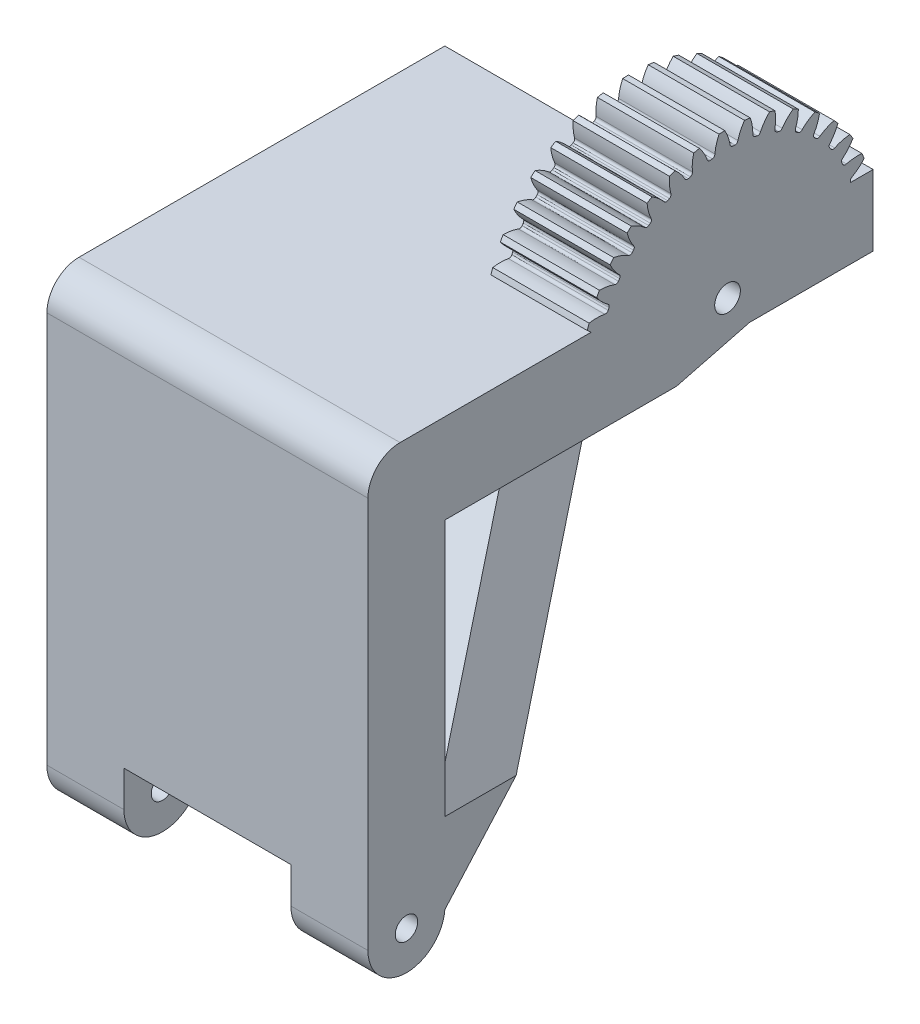
SolidWorks part; units mm, degrees
ref_plane "Front Plane" through (0, 0, 0) normal (0, 0, 1) x (1, 0, 0)
ref_plane "Top Plane" through (0, 0, 0) normal (0, 1, 0) x (1, 0, 0)
ref_plane "Right Plane" through (0, 0, 0) normal (1, 0, 0) x (0, 0, -1)
other "Graphic1"
sketch "Sketch2" plane through (0, 0, 0) normal (1, 0, 0) x (0, 0, -1)
  line L0 (-282, -50) -> (-282, 16.0062)
  line L1 (-282, 16.0062) -> (-203.3277, 16.0062)
  line L2 (-203.3277, 16.0062) -> (-203.3277, 4.9936)
  line L3 (-203.3277, 4.9936) -> (-222.5466, 4.9936)
  line L4 (-222.5466, 4.9936) -> (-233.9331, 2.0714)
  line L5 (-233.9331, 2.0714) -> (-233.9331, -9.6765)
  line L6 (-233.9331, -9.6765) -> (-270.0186, -50.4726)
  line L7 (-270.0186, 2.0714) -> (-270.0186, -35.8156)
  line L8 (-270.0186, -35.8156) -> (-240.3653, -2.4074)
  line L10 (-240.3653, -2.4074) -> (-240.3737, 1.8611)
  line L11 (-240.3737, 1.8611) -> (-270.0186, 2.0714)
  circle A0 centre (-276, -50) radius 1.75
  circle A1 centre (-226, 10) radius 2
  arc A2 (-282, -50) -> (-270.0186, -50.4726) centre (-276, -50) ccw
  point P24 (0, 0)
  point P25 (0, 0)
  point P26 (0, 0)
  point P29 (0, 0)
  point P32 (0, 0)
extrude "Boss-Extrude1" add sketch "Sketch2" along normal blind 47.5 and the other way blind 2.5 from offset 70
sketch "Sketch3" plane through (0, 0, 0) normal (0, 0, 1) x (1, 0, 0)
  line L0 (79.5, -55.8916) -> (79.5, -57.717)
  line L2 (79.5, -55.8916) -> (79.5, -44.4098)
  line L3 (79.5, -44.4098) -> (105.5, -44.4098)
  line L4 (105.5, -55.8916) -> (105.5, -44.4098)
  line L5 (79.5, -57.717) -> (105.5, -57.717)
  line L6 (105.5, -57.717) -> (105.5, -55.8916)
  point P8 (0, 0)
  point P9 (0, 0)
extrude "Cut-Extrude1" cut sketch "Sketch3" along normal through all
sketch "Sketch4" plane through (0, 0, 0) normal (0, 0, 1) x (1, 0, 0)
  line L0 (105.5, -44.4098) -> (94.3961, -22.2019)
  line L3 (90.6039, -22.2019) -> (79.5, -44.4098)
  line L4 (79.5, -44.4098) -> (105.5, -44.4098)
  line L5 (97.5, 2.0714) -> (117.5, -37.9286)
  line L6 (67.5, 2.0714) -> (117.5, 2.0714) construction
  line L7 (117.5, -50.4726) -> (117.5, -9.6765) construction
  line L8 (117.5, 2.0714) -> (97.5, 2.0714)
  line L9 (87.5, 2.0714) -> (67.5, 2.0714)
  line L10 (67.5, -9.6765) -> (67.5, 2.0714) construction
  line L11 (67.5, 2.0714) -> (67.5, -37.9286)
  line L12 (67.5, -50.4726) -> (67.5, -9.6765) construction
  line L13 (67.5, -37.9286) -> (87.5, 2.0714)
  line L14 (117.5, 2.0714) -> (117.5, -37.9286)
  line L15 (92.5, 16.0062) -> (92.5, -62.4116) construction
  line L16 (67.5, 16.0062) -> (117.5, 16.0062) construction
  line L17 (67.5, 16.0062) -> (67.5, -50) construction
  line L18 (117.5, 16.0062) -> (117.5, -50) construction
  arc A0 (94.3961, -22.2019) -> (90.6039, -22.2019) centre (92.5, -23.15) ccw
  dimension "D1" = 25
  dimension "D2" = 25
  dimension "D3" = 20
  dimension "D4" = 20
  dimension "D5" = 40
  dimension "D6" = 40
extrude "Cut-Extrude2" cut sketch "Sketch4" against normal blind 53 from surface at 270.0186 starting at face at (92.5, -16.8721, 270.0186)
fillet "Fillet1" radius 5 1 edges at (92.5, 16.0062, 282)
sketch "Sketch5" plane through (0, 16.0062, 0) normal (0, 1, 0) x (1, 0, 0)
  line L0 (65.0251, -220.0274) -> (95.5, -220.0314)
  line L1 (95.5, -220.0314) -> (102.5, -213.068)
  line L2 (102.5, -213.068) -> (102.5, -196.177)
  line L3 (102.5, -196.177) -> (65.0251, -196.177)
  line L4 (65.0251, -196.177) -> (65.0251, -220.0274)
  point P7 (0, 0)
  point P8 (0, 0)
extrude "Cut-Extrude3" cut sketch "Sketch5" against normal through all
sketch "Sketch7" plane through (117.5, 0, 0) normal (1, 0, 0) x (0, 0, -1)
  line L5 (-247.2493, 16.0062) -> (-206.8184, 16.0062)
  arc A0 (-222.9056, 32.589) -> (-222.459, 32.5234) centre (-226, 10) cw
  arc A1 (-221.7033, 29.6354) -> (-221.3907, 29.5644) centre (-226, 10) cw
  arc A2 (-219.0301, 31.7085) -> (-219.4613, 31.8423) centre (-226, 10) ccw
  arc A3 (-219.0301, 31.7085) -> (-218.6017, 31.5663) centre (-226, 10) cw
  arc A4 (-218.3589, 28.591) -> (-218.0634, 28.4667) centre (-226, 10) cw
  arc A5 (-215.3663, 30.1684) -> (-215.7678, 30.375) centre (-226, 10) ccw
  arc A6 (-215.3663, 30.1684) -> (-214.9691, 29.9539) centre (-226, 10) cw
  arc A7 (-215.2467, 26.9817) -> (-214.9773, 26.808) centre (-226, 10) cw
  arc A8 (-212.0257, 28.0155) -> (-212.3851, 28.2887) centre (-226, 10) ccw
  arc A9 (-212.0257, 28.0155) -> (-211.6717, 27.7353) centre (-226, 10) cw
  arc A10 (-212.4612, 24.8564) -> (-212.226, 24.6386) centre (-226, 10) cw
  arc A11 (-209.1096, 25.3152) -> (-209.4162, 25.6466) centre (-226, 10) ccw
  arc A12 (-209.1096, 25.3152) -> (-208.8097, 24.9778) centre (-226, 10) cw
  arc A13 (-210.0871, 22.2797) -> (-209.8933, 22.0244) centre (-226, 10) cw
  arc A14 (-206.7068, 22.1495) -> (-206.9511, 22.5292) centre (-226, 10) ccw
  arc A15 (-206.7068, 22.1495) -> (-206.47, 21.7652) centre (-226, 10) cw
  arc A16 (-208.1966, 19.3299) -> (-208.05, 19.0448) centre (-226, 10) cw
  arc A17 (-204.8901, 18.6147) -> (-205.0648, 19.031) centre (-226, 10) ccw
  arc A18 (-204.8901, 18.6147) -> (-204.7237, 18.1951) centre (-226, 10) cw
  arc A19 (-206.8469, 16.0966) -> (-206.8184, 16.0062) centre (-226, 10) cw
  arc A83 (-247.7085, 16.9699) -> (-247.8423, 16.5387) centre (-226, 10) ccw
  arc A84 (-247.7085, 16.9699) -> (-247.5663, 17.3984) centre (-226, 10) cw
  arc A85 (-244.591, 17.6411) -> (-244.4667, 17.9366) centre (-226, 10) cw
  arc A86 (-246.1684, 20.6337) -> (-246.375, 20.2323) centre (-226, 10) ccw
  arc A87 (-246.1684, 20.6337) -> (-245.9539, 21.0309) centre (-226, 10) cw
  arc A88 (-242.9817, 20.7533) -> (-242.808, 21.0228) centre (-226, 10) cw
  arc A89 (-244.0155, 23.9743) -> (-244.2887, 23.6149) centre (-226, 10) ccw
  arc A90 (-244.0155, 23.9743) -> (-243.7353, 24.3283) centre (-226, 10) cw
  arc A91 (-240.8564, 23.5388) -> (-240.6386, 23.774) centre (-226, 10) cw
  arc A92 (-241.3152, 26.8904) -> (-241.6466, 26.5838) centre (-226, 10) ccw
  arc A93 (-241.3152, 26.8904) -> (-240.9778, 27.1903) centre (-226, 10) cw
  arc A94 (-238.2797, 25.9129) -> (-238.0244, 26.1067) centre (-226, 10) cw
  arc A95 (-238.1495, 29.2932) -> (-238.5292, 29.0489) centre (-226, 10) ccw
  arc A96 (-238.1495, 29.2932) -> (-237.7652, 29.53) centre (-226, 10) cw
  arc A97 (-235.3299, 27.8035) -> (-235.0448, 27.95) centre (-226, 10) cw
  arc A98 (-234.6147, 31.1099) -> (-235.031, 30.9352) centre (-226, 10) ccw
  arc A99 (-234.6147, 31.1099) -> (-234.1951, 31.2763) centre (-226, 10) cw
  arc A100 (-232.0966, 29.1531) -> (-231.7904, 29.2479) centre (-226, 10) cw
  arc A101 (-230.8182, 32.2851) -> (-231.2585, 32.1853) centre (-226, 10) ccw
  arc A102 (-230.8182, 32.2851) -> (-230.376, 32.3761) centre (-226, 10) cw
  arc A103 (-228.6781, 29.9208) -> (-228.3601, 29.961) centre (-226, 10) cw
  arc A104 (-226.8752, 32.7832) -> (-227.3261, 32.7614) centre (-226, 10) ccw
  arc A105 (-226.8752, 32.7832) -> (-226.4239, 32.7961) centre (-226, 10) cw
  arc A106 (-225.1782, 30.0832) -> (-224.858, 30.0675) centre (-226, 10) cw
  arc A107 (-222.9056, 32.589) -> (-223.3535, 32.6459) centre (-226, 10) ccw
  arc A108 (-206.0792, 12.6781) -> (-206.039, 12.3601) centre (-226, 10) cw [skipped]
  arc A109 (-203.2168, 10.8752) -> (-203.2386, 11.3261) centre (-226, 10) ccw [skipped]
  arc A110 (-203.2168, 10.8752) -> (-203.2039, 10.4239) centre (-226, 10) cw [skipped]
  arc A111 (-205.9168, 9.1782) -> (-205.9325, 8.858) centre (-226, 10) cw [skipped]
  arc A112 (-203.411, 6.9056) -> (-203.3541, 7.3535) centre (-226, 10) ccw [skipped]
  arc A113 (-203.411, 6.9056) -> (-203.4767, 6.459) centre (-226, 10) cw [skipped]
  arc A114 (-206.3646, 5.7033) -> (-206.4356, 5.3907) centre (-226, 10) cw [skipped]
  arc A115 (-204.2915, 3.0301) -> (-204.1577, 3.4613) centre (-226, 10) ccw [skipped]
  arc A116 (-204.2915, 3.0301) -> (-204.4337, 2.6017) centre (-226, 10) cw [skipped]
  arc A117 (-207.4091, 2.3589) -> (-207.5333, 2.0634) centre (-226, 10) cw [skipped]
  arc A118 (-205.8316, -0.6337) -> (-205.625, -0.2322) centre (-226, 10) ccw [skipped]
  arc A119 (-205.8316, -0.6337) -> (-206.0461, -1.0309) centre (-226, 10) cw [skipped]
  arc A120 (-209.0184, -0.7533) -> (-209.192, -1.0227) centre (-226, 10) cw [skipped]
  arc A121 (-207.9845, -3.9743) -> (-207.7114, -3.6149) centre (-226, 10) ccw [skipped]
  arc A122 (-207.9845, -3.9743) -> (-208.2647, -4.3283) centre (-226, 10) cw [skipped]
  arc A123 (-211.1436, -3.5388) -> (-211.3614, -3.774) centre (-226, 10) cw [skipped]
  arc A124 (-210.6848, -6.8904) -> (-210.3534, -6.5838) centre (-226, 10) ccw [skipped]
  arc A125 (-210.6848, -6.8904) -> (-211.0222, -7.1903) centre (-226, 10) cw [skipped]
  arc A126 (-213.7203, -5.9129) -> (-213.9757, -6.1067) centre (-226, 10) cw [skipped]
  arc A127 (-213.8505, -9.2932) -> (-213.4709, -9.0489) centre (-226, 10) ccw [skipped]
  arc A128 (-213.8505, -9.2932) -> (-214.2348, -9.53) centre (-226, 10) cw [skipped]
  arc A129 (-216.6701, -7.8035) -> (-216.9552, -7.95) centre (-226, 10) cw [skipped]
  arc A130 (-217.3853, -11.1099) -> (-216.969, -10.9352) centre (-226, 10) ccw [skipped]
  arc A131 (-217.3853, -11.1099) -> (-217.8049, -11.2763) centre (-226, 10) cw [skipped]
  arc A132 (-219.9034, -9.1531) -> (-220.2096, -9.2479) centre (-226, 10) cw [skipped]
  arc A133 (-221.1818, -12.2851) -> (-220.7416, -12.1853) centre (-226, 10) ccw [skipped]
  arc A134 (-221.1818, -12.2851) -> (-221.624, -12.3761) centre (-226, 10) cw [skipped]
  arc A135 (-223.3219, -9.9208) -> (-223.6399, -9.961) centre (-226, 10) cw [skipped]
  arc A136 (-225.1248, -12.7832) -> (-224.6739, -12.7614) centre (-226, 10) ccw [skipped]
  arc A137 (-225.1248, -12.7832) -> (-225.5761, -12.7961) centre (-226, 10) cw [skipped]
  arc A138 (-226.8218, -10.0832) -> (-227.142, -10.0675) centre (-226, 10) cw [skipped]
  arc A139 (-229.0944, -12.589) -> (-228.6465, -12.6459) centre (-226, 10) ccw [skipped]
  arc A140 (-229.0944, -12.589) -> (-229.541, -12.5233) centre (-226, 10) cw [skipped]
  arc A141 (-230.2967, -9.6354) -> (-230.6093, -9.5644) centre (-226, 10) cw [skipped]
  arc A142 (-232.9699, -11.7085) -> (-232.5387, -11.8423) centre (-226, 10) ccw [skipped]
  arc A143 (-232.9699, -11.7085) -> (-233.3984, -11.5663) centre (-226, 10) cw [skipped]
  arc A144 (-233.6411, -8.591) -> (-233.9366, -8.4667) centre (-226, 10) cw [skipped]
  arc A145 (-236.6337, -10.1684) -> (-236.2323, -10.375) centre (-226, 10) ccw [skipped]
  arc A146 (-236.6337, -10.1684) -> (-237.0309, -9.9539) centre (-226, 10) cw [skipped]
  arc A147 (-236.7533, -6.9817) -> (-237.0228, -6.808) centre (-226, 10) cw [skipped]
  arc A148 (-239.9743, -8.0155) -> (-239.6149, -8.2887) centre (-226, 10) ccw [skipped]
  arc A149 (-239.9743, -8.0155) -> (-240.3283, -7.7353) centre (-226, 10) cw [skipped]
  arc A150 (-239.5388, -4.8564) -> (-239.774, -4.6386) centre (-226, 10) cw [skipped]
  arc A151 (-242.8904, -5.3152) -> (-242.5838, -5.6466) centre (-226, 10) ccw [skipped]
  arc A152 (-242.8904, -5.3152) -> (-243.1903, -4.9778) centre (-226, 10) cw [skipped]
  arc A153 (-241.9129, -2.2797) -> (-242.1067, -2.0244) centre (-226, 10) cw [skipped]
  arc A154 (-245.2932, -2.1495) -> (-245.0489, -2.5291) centre (-226, 10) ccw [skipped]
  arc A155 (-245.2932, -2.1495) -> (-245.53, -1.7652) centre (-226, 10) cw [skipped]
  arc A156 (-243.8035, 0.6701) -> (-243.95, 0.9552) centre (-226, 10) cw [skipped]
  arc A157 (-247.1099, 1.3853) -> (-246.9352, 0.969) centre (-226, 10) ccw [skipped]
  arc A158 (-247.1099, 1.3853) -> (-247.2763, 1.8049) centre (-226, 10) cw [skipped]
  arc A159 (-245.1531, 3.9034) -> (-245.2479, 4.2096) centre (-226, 10) cw [skipped]
  arc A160 (-248.2851, 5.1818) -> (-248.1853, 4.7416) centre (-226, 10) ccw [skipped]
  arc A161 (-248.2851, 5.1818) -> (-248.3761, 5.624) centre (-226, 10) cw [skipped]
  arc A162 (-245.9208, 7.3219) -> (-245.961, 7.6399) centre (-226, 10) cw [skipped]
  arc A163 (-248.7832, 9.1248) -> (-248.7614, 8.6739) centre (-226, 10) ccw [skipped]
  arc A164 (-248.7832, 9.1248) -> (-248.7961, 9.5761) centre (-226, 10) cw [skipped]
  arc A165 (-246.0832, 10.8218) -> (-246.0675, 11.142) centre (-226, 10) cw [skipped]
  arc A166 (-248.5891, 13.0944) -> (-248.6459, 12.6465) centre (-226, 10) ccw [skipped]
  arc A167 (-248.5891, 13.0944) -> (-248.5234, 13.541) centre (-226, 10) cw [skipped]
  arc A168 (-245.6354, 14.2967) -> (-245.5644, 14.6093) centre (-226, 10) cw [skipped]
  arc A169 (-203.7149, 14.8182) -> (-203.8147, 15.2584) centre (-226, 10) ccw [skipped]
  arc A170 (-203.7149, 14.8182) -> (-203.6239, 14.376) centre (-226, 10) cw [skipped]
  spline S0 degree 2 poles (-222.459, 32.5234) (-222.0472, 31.3598) (-222.0503, 30.123) knots 0 0 0 1 1 1
  spline S1 degree 2 poles (-222.0503, 30.123) (-222.0649, 29.7407) (-221.7033, 29.6354) knots 0 0 0 1 1 1
  spline S2 degree 2 poles (-220.867, 29.8542) (-221.019, 29.503) (-221.3907, 29.5644) knots 0 0 0 1 1 1
  spline S3 degree 2 poles (-219.4613, 31.8423) (-220.3354, 30.9709) (-220.867, 29.8542) knots 0 0 0 1 1 1
  spline S4 degree 2 poles (-218.6017, 31.5663) (-218.3982, 30.3489) (-218.616, 29.1315) knots 0 0 0 1 1 1
  spline S5 degree 2 poles (-218.616, 29.1315) (-218.6968, 28.7574) (-218.3589, 28.591) knots 0 0 0 1 1 1
  spline S6 degree 2 poles (-217.4973, 28.6612) (-217.708, 28.3418) (-218.0634, 28.4667) knots 0 0 0 1 1 1
  spline S7 degree 2 poles (-215.7678, 30.375) (-216.7799, 29.6687) (-217.4973, 28.6612) knots 0 0 0 1 1 1
  spline S8 degree 2 poles (-214.9691, 29.9539) (-214.9801, 28.7197) (-215.4061, 27.5586) knots 0 0 0 1 1 1
  spline S9 degree 2 poles (-215.4061, 27.5586) (-215.5506, 27.2043) (-215.2467, 26.9817) knots 0 0 0 1 1 1
  spline S10 degree 2 poles (-214.386, 26.9012) (-214.649, 26.6233) (-214.9773, 26.808) knots 0 0 0 1 1 1
  spline S11 degree 2 poles (-212.3851, 28.2887) (-213.5046, 27.7688) (-214.386, 26.9012) knots 0 0 0 1 1 1
  spline S12 degree 2 poles (-211.6717, 27.7353) (-211.8969, 26.5217) (-212.518, 25.4522) knots 0 0 0 1 1 1
  spline S13 degree 2 poles (-212.518, 25.4522) (-212.7218, 25.1284) (-212.4612, 24.8564) knots 0 0 0 1 1 1
  spline S14 degree 2 poles (-211.6276, 24.6277) (-211.9348, 24.3996) (-212.226, 24.6386) knots 0 0 0 1 1 1
  spline S15 degree 2 poles (-209.4162, 25.6466) (-210.6089, 25.329) (-211.6276, 24.6277) knots 0 0 0 1 1 1
  spline S16 degree 2 poles (-208.8097, 24.9778) (-209.2422, 23.8217) (-210.0396, 22.8763) knots 0 0 0 1 1 1
  spline S17 degree 2 poles (-210.0396, 22.8763) (-210.2965, 22.5928) (-210.0871, 22.2797) knots 0 0 0 1 1 1
  spline S18 degree 2 poles (-209.3059, 21.9097) (-209.6481, 21.7385) (-209.8933, 22.0244) knots 0 0 0 1 1 1
  spline S19 degree 2 poles (-206.9511, 22.5292) (-208.1808, 22.4235) (-209.3059, 21.9097) knots 0 0 0 1 1 1
  spline S20 degree 2 poles (-206.47, 21.7652) (-207.0966, 20.7018) (-208.0461, 19.9092) knots 0 0 0 1 1 1
  spline S21 degree 2 poles (-208.0461, 19.9092) (-208.3484, 19.6746) (-208.1966, 19.3299) knots 0 0 0 1 1 1
  spline S22 degree 2 poles (-207.4914, 18.8299) (-207.8581, 18.7207) (-208.05, 19.0448) knots 0 0 0 1 1 1
  spline S23 degree 2 poles (-205.0648, 19.031) (-206.2942, 19.1405) (-207.4914, 18.8299) knots 0 0 0 1 1 1
  spline S24 degree 2 poles (-204.7237, 18.1951) (-205.5255, 17.2567) (-206.5981, 16.641) knots 0 0 0 1 1 1
  spline S25 degree 2 poles (-206.5981, 16.641) (-206.9366, 16.4625) (-206.8469, 16.0966) knots 0 0 0 1 1 1
  spline S111 degree 2 poles (-247.8423, 16.5387) (-247.5588, 16.2543) (-247.2493, 16.0062) knots 0 0 0 0.325355 0.325355 0.325355
  spline S112 degree 2 poles (-247.5663, 17.3984) (-246.3489, 17.6019) (-245.1315, 17.384) knots 0 0 0 1 1 1
  spline S113 degree 2 poles (-245.1315, 17.384) (-244.7574, 17.3032) (-244.591, 17.6411) knots 0 0 0 1 1 1
  spline S114 degree 2 poles (-244.6612, 18.5027) (-244.3418, 18.292) (-244.4667, 17.9366) knots 0 0 0 1 1 1
  spline S115 degree 2 poles (-246.375, 20.2323) (-245.6687, 19.2201) (-244.6612, 18.5027) knots 0 0 0 1 1 1
  spline S116 degree 2 poles (-245.9539, 21.0309) (-244.7197, 21.0199) (-243.5586, 20.594) knots 0 0 0 1 1 1
  spline S117 degree 2 poles (-243.5586, 20.594) (-243.2043, 20.4494) (-242.9817, 20.7533) knots 0 0 0 1 1 1
  spline S118 degree 2 poles (-242.9012, 21.614) (-242.6233, 21.351) (-242.808, 21.0228) knots 0 0 0 1 1 1
  spline S119 degree 2 poles (-244.2887, 23.6149) (-243.7688, 22.4954) (-242.9012, 21.614) knots 0 0 0 1 1 1
  spline S120 degree 2 poles (-243.7353, 24.3283) (-242.5217, 24.1031) (-241.4522, 23.482) knots 0 0 0 1 1 1
  spline S121 degree 2 poles (-241.4522, 23.482) (-241.1284, 23.2782) (-240.8564, 23.5388) knots 0 0 0 1 1 1
  spline S122 degree 2 poles (-240.6277, 24.3724) (-240.3996, 24.0652) (-240.6386, 23.774) knots 0 0 0 1 1 1
  spline S123 degree 2 poles (-241.6466, 26.5838) (-241.3291, 25.3911) (-240.6277, 24.3724) knots 0 0 0 1 1 1
  spline S124 degree 2 poles (-240.9778, 27.1903) (-239.8218, 26.7579) (-238.8763, 25.9605) knots 0 0 0 1 1 1
  spline S125 degree 2 poles (-238.8763, 25.9605) (-238.5928, 25.7035) (-238.2797, 25.9129) knots 0 0 0 1 1 1
  spline S126 degree 2 poles (-237.9097, 26.6941) (-237.7385, 26.352) (-238.0244, 26.1067) knots 0 0 0 1 1 1
  spline S127 degree 2 poles (-238.5292, 29.0489) (-238.4235, 27.8192) (-237.9097, 26.6941) knots 0 0 0 1 1 1
  spline S128 degree 2 poles (-237.7652, 29.53) (-236.7018, 28.9034) (-235.9092, 27.9539) knots 0 0 0 1 1 1
  spline S129 degree 2 poles (-235.9092, 27.9539) (-235.6746, 27.6516) (-235.3299, 27.8035) knots 0 0 0 1 1 1
  spline S130 degree 2 poles (-234.8299, 28.5086) (-234.7207, 28.1419) (-235.0448, 27.95) knots 0 0 0 1 1 1
  spline S131 degree 2 poles (-235.031, 30.9352) (-235.1405, 29.7058) (-234.8299, 28.5086) knots 0 0 0 1 1 1
  spline S132 degree 2 poles (-234.1951, 31.2763) (-233.2567, 30.4745) (-232.641, 29.4019) knots 0 0 0 1 1 1
  spline S133 degree 2 poles (-232.641, 29.4019) (-232.4625, 29.0634) (-232.0966, 29.1531) knots 0 0 0 1 1 1
  spline S134 degree 2 poles (-231.4818, 29.7607) (-231.4379, 29.3806) (-231.7904, 29.2479) knots 0 0 0 1 1 1
  spline S135 degree 2 poles (-231.2585, 32.1853) (-231.5798, 30.9936) (-231.4818, 29.7607) knots 0 0 0 1 1 1
  spline S136 degree 2 poles (-230.376, 32.3761) (-229.5911, 31.4236) (-229.171, 30.2603) knots 0 0 0 1 1 1
  spline S137 degree 2 poles (-229.171, 30.2603) (-229.054, 29.896) (-228.6781, 29.9208) knots 0 0 0 1 1 1
  spline S138 degree 2 poles (-227.9671, 30.4124) (-227.9899, 30.0304) (-228.3601, 29.961) knots 0 0 0 1 1 1
  spline S139 degree 2 poles (-227.3261, 32.7614) (-227.8495, 31.6436) (-227.9671, 30.4124) knots 0 0 0 1 1 1
  spline S140 degree 2 poles (-226.4239, 32.7961) (-225.8163, 31.7217) (-225.6047, 30.5032) knots 0 0 0 1 1 1
  spline S141 degree 2 poles (-225.6047, 30.5032) (-225.5527, 30.1241) (-225.1782, 30.0832) knots 0 0 0 1 1 1
  spline S142 degree 2 poles (-224.3926, 30.4439) (-224.4814, 30.0717) (-224.858, 30.0675) knots 0 0 0 1 1 1
  spline S143 degree 2 poles (-223.3535, 32.6459) (-224.063, 31.636) (-224.3926, 30.4439) knots 0 0 0 1 1 1
  dimension "D6" = 36
extrude "Boss-Extrude2" add sketch "Sketch7" against normal blind 15
